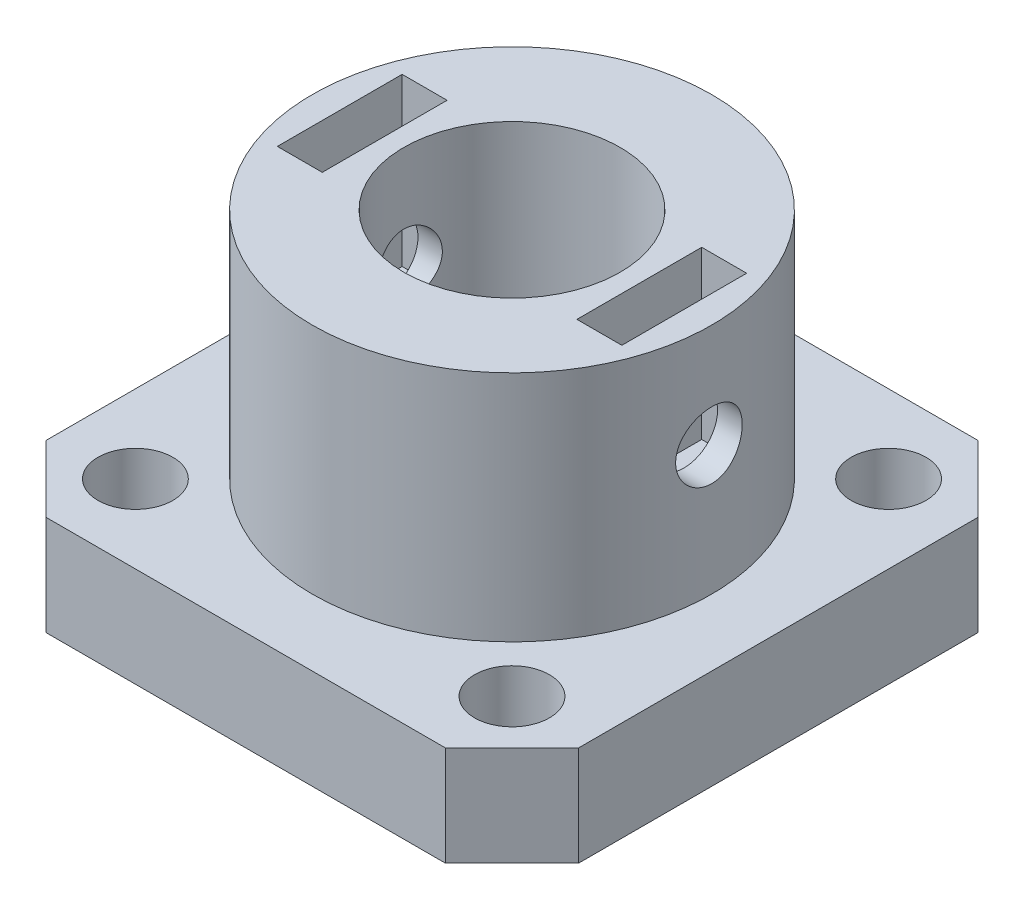
SolidWorks part; units mm, degrees
ref_plane "Front Plane" through (0, 0, 0) normal (0, 0, 1) x (1, 0, 0)
ref_plane "Top Plane" through (0, 0, 0) normal (0, 1, 0) x (1, 0, 0)
ref_plane "Right Plane" through (0, 0, 0) normal (1, 0, 0) x (0, 0, -1)
sketch "Sketch1" plane through (0, 0, 0) normal (0, 1, 0) x (1, 0, 0)
  circle A0 centre (0, 0) radius 12
  circle A1 centre (0, 0) radius 6.5
  dimension "D1" = 24
  dimension "D2" = 13
extrude "Boss-Extrude1" add sketch "Sketch1" along normal blind 20
sketch "Sketch2" plane through (0, 0, 0) normal (0, 1, 0) x (1, 0, 0)
  line L1 (-16, 16) -> (16, 16)
  line L2 (-16, 16) -> (-16, -16)
  line L3 (-16, -16) -> (16, -16)
  line L4 (16, 16) -> (16, -16)
  line L5 (-16, 16) -> (16, -16) construction
  line L6 (-16, -16) -> (16, 16) construction
  circle A0 centre (0, 0) radius 14.1471 construction
  circle A1 centre (0, 0) radius 6.5
  point P0 (0, 0)
  dimension "D3" = 13
  dimension "D1" = 32
  dimension "D2" = 32
extrude "Boss-Extrude2" add sketch "Sketch2" along normal blind 6
sketch "Sketch3" plane through (0, 0, 0) normal (0, 1, 0) x (1, 0, 0)
  line L1 (-11.3137, 11.3137) -> (11.3137, 11.3137) construction
  line L2 (-11.3137, 11.3137) -> (-11.3137, -11.3137) construction
  line L3 (-11.3137, -11.3137) -> (11.3137, -11.3137) construction
  line L4 (11.3137, 11.3137) -> (11.3137, -11.3137) construction
  line L5 (-11.3137, 11.3137) -> (11.3137, -11.3137) construction
  line L6 (-11.3137, -11.3137) -> (11.3137, 11.3137) construction
  circle A0 centre (-11.3137, 11.3137) radius 2.25
  circle A1 centre (-11.3137, -11.3137) radius 2.25
  circle A2 centre (11.3137, -11.3137) radius 2.25
  circle A3 centre (11.3137, 11.3137) radius 2.25
  circle A4 centre (0, 0) radius 16 construction
  point P0 (0, 0)
  dimension "D2" = 32
  dimension "D1" = 4.5
extrude "Cut-Extrude1" cut sketch "Sketch3" along normal through all
chamfer "Chamfer1" distance 4 angle 45 4 edges at (16, 3, -16) (16, 3, 16) (-16, 3, 16) (-16, 3, -16)
sketch "Sketch4" plane through (0, 0, 0) normal (0, 1, 0) x (1, 0, 0)
  line L0 (0, 0) -> (-9, 0) construction
  line L1 (-10.35, 3.75) -> (-7.65, 3.75)
  line L2 (-10.35, 3.75) -> (-10.35, -3.75)
  line L3 (-10.35, -3.75) -> (-7.65, -3.75)
  line L4 (-7.65, 3.75) -> (-7.65, -3.75)
  line L5 (-10.35, 3.75) -> (-7.65, -3.75) construction
  line L6 (-10.35, -3.75) -> (-7.65, 3.75) construction
  point P0 (-9, 0)
  dimension "D1" = 7.5
  dimension "D2" = 2.7
  dimension "D3" = 9
extrude "Cut-Extrude2" cut sketch "Sketch4" against normal blind 10 from surface at 20 starting at face at (0, 20, 12)
sketch "Sketch5" plane through (0, 0, 0) normal (1, 0, 0) x (0, 0, -1)
  line L1 (-3.75, 17.5) -> (3.75, 17.5) construction
  line L2 (-3.75, 17.5) -> (-3.75, 10) construction
  line L3 (-3.75, 10) -> (3.75, 10) construction
  line L4 (3.75, 17.5) -> (3.75, 10) construction
  line L5 (-3.75, 17.5) -> (3.75, 10) construction
  line L6 (-3.75, 10) -> (3.75, 17.5) construction
  circle A0 centre (0, 13.75) radius 2
  point P0 (0, 13.75)
  dimension "D2" = 4
  dimension "D1" = 7.5
extrude "Cut-Extrude3" cut sketch "Sketch5" against normal through all both and the other way through all
mirror "Mirror1" about plane through (0, 0, 0) normal (1, 0, 0) of "Cut-Extrude2"
equation "\"dmin\"= 13"
equation "\"dmax\"= 24"
equation "\"l\"= 20"
equation "\"k\"= 32"
equation "\"b\"= 6"
equation "\"holespace\"= 32"
equation "\"holes\"= 4.5"
equation "\"D1@Boss-Extrude1\"=\"l\""
equation "\"D2@Sketch1\"=\"dmin\""
equation "\"D1@Sketch1\"=\"dmax\""
equation "\"D3@Sketch2\"=\"dmin\""
equation "\"D1@Sketch2\"=\"k\""
equation "\"D2@Sketch2\"=\"k\""
equation "\"D1@Boss-Extrude2\"=\"b\""
equation "\"D2@Sketch3\"=\"holespace\""
equation "\"D1@Sketch3\"=\"holes\""
equation "\"chamfer\"= 4"
equation "\"D1@Chamfer1\"=\"chamfer\""
